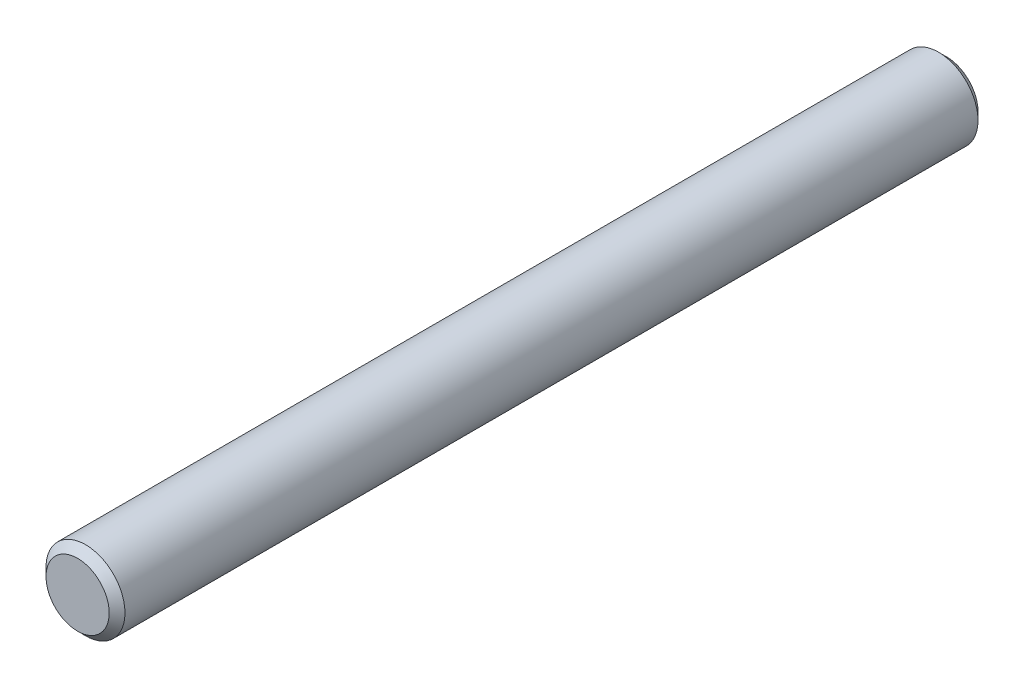
SolidWorks part; units mm, degrees
ref_plane "Plano frontal" through (0, 0, 0) normal (0, 0, 1) x (1, 0, 0)
ref_plane "Plano superior" through (0, 0, 0) normal (0, 1, 0) x (1, 0, 0)
ref_plane "Plano direito" through (0, 0, 0) normal (1, 0, 0) x (0, 0, -1)
sketch "Esboço1" plane through (0, 0, 0) normal (0, 0, 1) x (1, 0, 0)
  circle A0 centre (0, 0) radius 2.5
  dimension "D1" = 5
extrude "Ressalto-extrusão1" add sketch "Esboço1" along normal blind 55
ref_plane "Plano1" through (0, 0, 33) normal (0, 0, 1) x (1, 0, 0)
chamfer "Chanfro1" distance 0.5 angle 45 2 edges at (2.5, 0, 0) (2.5, 0, 55)
